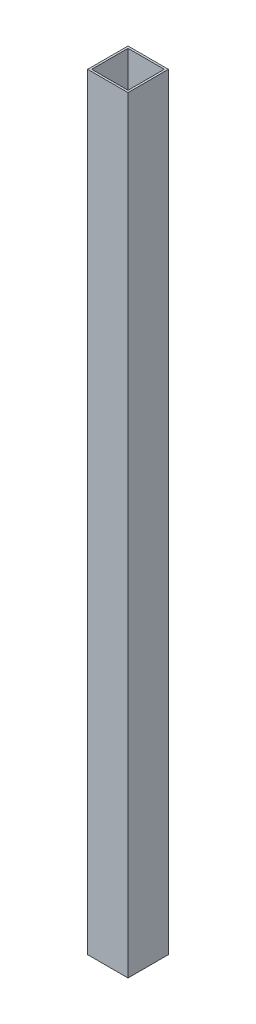
SolidWorks part; units mm, degrees
ref_plane "Front Plane" through (0, 0, 0) normal (0, 0, 1) x (1, 0, 0)
ref_plane "Top Plane" through (0, 0, 0) normal (0, 1, 0) x (1, 0, 0)
ref_plane "Right Plane" through (0, 0, 0) normal (1, 0, 0) x (0, 0, -1)
sketch "Sketch1" plane through (0, 0, 0) normal (0, 1, 0) x (1, 0, 0)
  line L0 (0, 0) -> (0, 25.4)
  line L1 (0, 25.4) -> (25.4, 25.4)
  line L2 (25.4, 25.4) -> (25.4, 0)
  line L3 (25.4, 0) -> (0, 0)
  line L6 (1.27, 12.3615) -> (1.27, 24.13)
  line L7 (1.27, 24.13) -> (12.7, 24.13)
  line L10 (12.7, 24.13) -> (24.13, 24.13)
  line L11 (24.13, 24.13) -> (24.13, 12.7)
  line L12 (24.13, 1.27) -> (24.13, 12.7)
  line L13 (24.13, 1.27) -> (12.7, 1.27)
  line L14 (1.27, 1.27) -> (12.7, 1.27)
  line L15 (1.27, 12.3615) -> (1.27, 1.27)
  dimension "D1" = 25.4
  dimension "D2" = 25.4
  dimension "D3" = 11.7685
  dimension "D4" = 11.0915
  dimension "D5" = 11.43
  dimension "D6" = 11.43
extrude "Boss-Extrude1" add sketch "Sketch1" along normal blind 482.6
sketch "Sketch2" plane through (0, 0, -25.4) normal (0, 0, -1) x (-1, 0, 0)
  circle A2 centre (-12.7, 50.8748) radius 2.54
extrude "Cut-Extrude1" cut sketch "Sketch2" against normal blind 2.54
